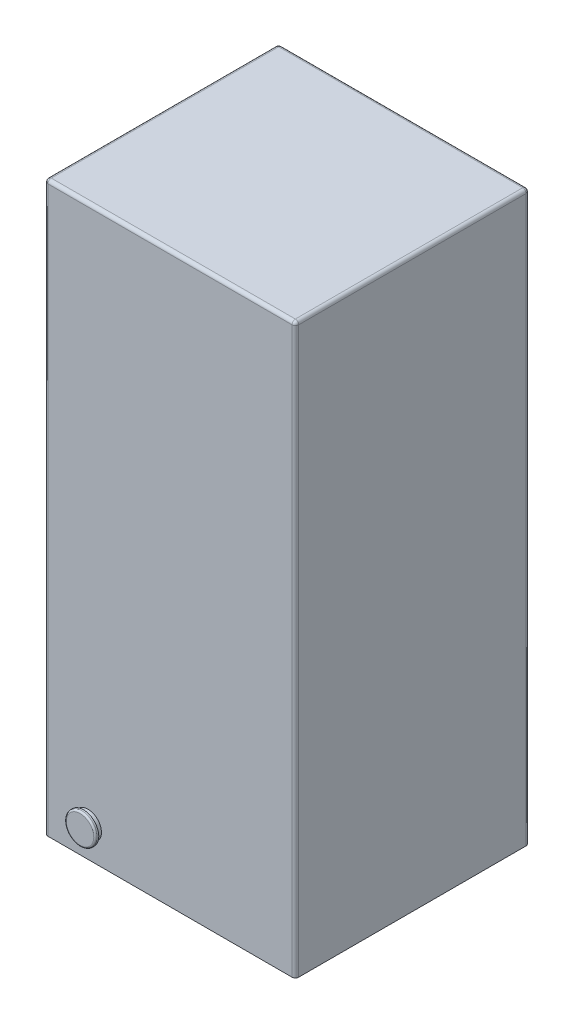
SolidWorks part; units mm, degrees
ref_plane "Alzado" through (0, 0, 0) normal (0, 0, 1) x (1, 0, 0)
ref_plane "Planta" through (0, 0, 0) normal (0, 1, 0) x (1, 0, 0)
ref_plane "Vista lateral" through (0, 0, 0) normal (1, 0, 0) x (0, 0, -1)
sketch "Croquis1" plane through (0, 0, 0) normal (0, 0, 1) x (1, 0, 0)
  line L1 (0, 0) -> (750, 0)
  line L2 (0, 0) -> (0, -1700)
  line L3 (0, -1700) -> (750, -1700)
  line L4 (750, 0) -> (750, -1700)
  dimension "D1" = 1700
  dimension "D2" = 750
extrude "Saliente-Extruir1" add sketch "Croquis1" along normal blind 700
fillet "Redondeo1" radius 10 8 edges at (0, -850, 0) (375, 0, 0) (750, -850, 0) (0, 0, 350) (0, -850, 700) (375, 0, 700) (750, 0, 350) (750, -850, 700)
sketch "Croquis2" plane through (0, 0, 700) normal (0, 0, 1) x (1, 0, 0)
  line L0 (10, -10) -> (10, -1700) construction
  line L1 (10, -1700) -> (740, -1700) construction
  circle A0 centre (130, -1610) radius 40
  dimension "D1" = 80
  dimension "D3" = 90
  dimension "D2" = 120
extrude "Saliente-Extruir2" add sketch "Croquis2" along normal blind 24
sketch "Croquis3" plane through (0, 0, 724) normal (0, 0, 1) x (1, 0, 0)
  circle A0 centre (130, -1610) radius 46
  dimension "D1" = 92
extrude "Saliente-Extruir3" add sketch "Croquis3" against normal blind 10
fillet "Redondeo2" radius 5 1 edges at (176, -1610, 724)
